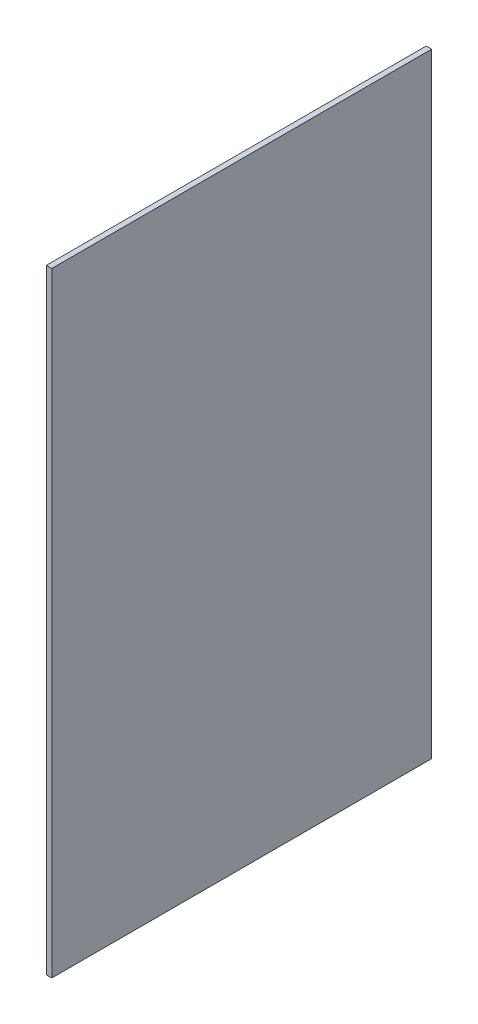
SolidWorks part; units mm, degrees
ref_plane "Alzado" through (0, 0, 0) normal (0, 0, 1) x (1, 0, 0)
ref_plane "Planta" through (0, 0, 0) normal (0, 1, 0) x (1, 0, 0)
ref_plane "Vista lateral" through (0, 0, 0) normal (1, 0, 0) x (0, 0, -1)
sketch "Croquis1" plane through (0, 0, 0) normal (0, 0, 1) x (1, 0, 0)
  line L0 (450, 81.3) -> (450, 450) construction
  line L1 (453.3, 453.3) -> (450, 453.3)
  line L4 (450, 81.3) -> (450, 453.3)
  line L5 (453.3, 81.3) -> (453.3, 453.3)
  line L7 (450, 81.3) -> (453.3, 81.3)
  line L9 (-3.3, 453.3) -> (453.3, 453.3) construction
  line L10 (0, 450) -> (450, 450) construction
  line L11 (0, 0) -> (0, 450) construction
  line L12 (-3.3, 0) -> (-3.3, 453.3) construction
  dimension "D1" = 372
  dimension "D3" = 3.3
extrude "Saliente-Extruir2" add sketch "Croquis1" along normal blind 230
